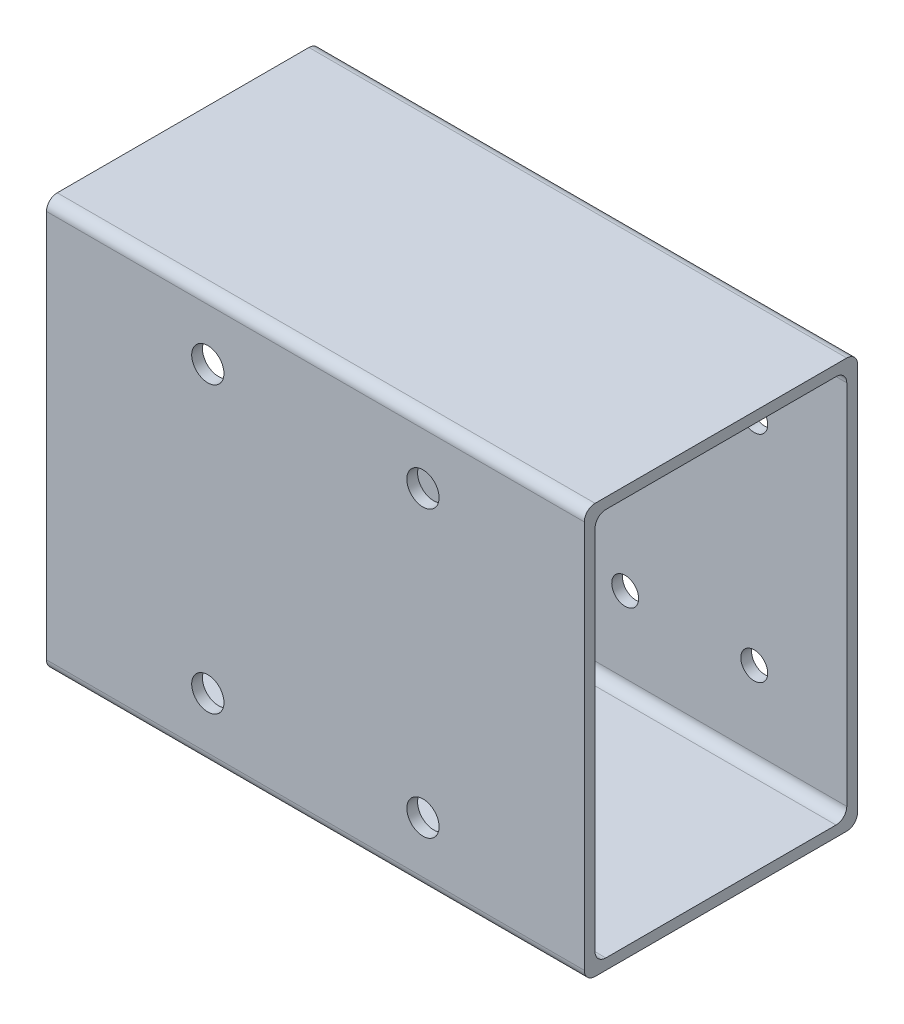
SolidWorks part; units mm, degrees
material "A500"
ref_plane "Alzado" through (0, 0, 0) normal (0, 0, 1) x (1, 0, 0)
ref_plane "Planta" through (0, 0, 0) normal (0, 1, 0) x (1, 0, 0)
ref_plane "Vista lateral" through (0, 0, 0) normal (1, 0, 0) x (0, 0, -1)
sketch "Sketch1" plane through (0, 0, 0) normal (1, 0, 0) x (0, 0, -1)
  line L1 (25.4, 38.1) -> (-25.4, 38.1)
  line L2 (25.4, 38.1) -> (25.4, -38.1)
  line L3 (25.4, -38.1) -> (-25.4, -38.1)
  line L4 (-25.4, 38.1) -> (-25.4, -38.1)
  line L5 (25.4, 38.1) -> (-25.4, -38.1) construction
  line L6 (25.4, -38.1) -> (-25.4, 38.1) construction
  point P0 (0, 0)
  dimension "D1" = 76.2
  dimension "D2" = 50.8
extrude "Boss-Extrude1" add sketch "Sketch1" against normal blind 100
sketch "Sketch2" plane through (0, 0, 0) normal (1, 0, 0) x (0, 0, -1)
  line L0 (25.4, 38.1) -> (-25.4, 38.1) construction
  line L1 (23.4, 36.1) -> (-23.4, 36.1)
  line L2 (23.4, 36.1) -> (23.4, -36.1)
  line L3 (23.4, -36.1) -> (-23.4, -36.1)
  line L4 (-23.4, 36.1) -> (-23.4, -36.1)
  line L5 (23.4, 36.1) -> (-23.4, -36.1) construction
  line L6 (23.4, -36.1) -> (-23.4, 36.1) construction
  line L7 (25.4, -38.1) -> (25.4, 38.1) construction
  point P0 (0, 0)
  dimension "D1" = 2
  dimension "D2" = 2
extrude "Cut-Extrude1" cut sketch "Sketch2" against normal through all
fillet "Fillet2" radius 2 8 edges at (-50, -38.1, -25.4) (-50, -38.1, 25.4) (-50, 38.1, 25.4) (-50, 38.1, -25.4) (-50, -36.1, -23.4) (-50, 36.1, -23.4) (-50, -36.1, 23.4) (-50, 36.1, 23.4)
sketch "Croquis2" plane through (0, 0, 25.4) normal (0, 0, 1) x (1, 0, 0)
  line L0 (-50, 36.1) -> (-50, -36.1) construction
  line L1 (0, 36.1) -> (-100, 36.1) construction
  line L2 (-100, -36.1) -> (0, -36.1) construction
  line L4 (-30, 26.5) -> (-70, 26.5)
  line L5 (-30, 26.5) -> (-30, -26.5)
  line L6 (-30, -26.5) -> (-70, -26.5)
  line L7 (-70, 26.5) -> (-70, -26.5)
  line L8 (-30, 26.5) -> (-70, -26.5) construction
  line L9 (-30, -26.5) -> (-70, 26.5) construction
  circle A0 centre (-70, 26.5) radius 3
  circle A1 centre (-30, 26.5) radius 3
  circle A2 centre (-30, -26.5) radius 3
  circle A3 centre (-70, -26.5) radius 3
  point P6 (-50, 0)
  dimension "D3" = 6
  dimension "D4" = 6
  dimension "D5" = 6
  dimension "D6" = 6
  dimension "D1" = 53
  dimension "D2" = 40
extrude "Cortar-Extruir2" cut sketch "Croquis2" against normal blind 10 contours L5 A1 L4 | L4 A1 L5 | L4 A0 L7 | L7 A0 L4 | L6 A3 L7 | L7 A3 L6 | L6 A2 L5 | L5 A2 L6
sketch "Croquis4" plane through (0, 0, -25.4) normal (0, 0, -1) x (-1, 0, 0)
  line L0 (49.2, 38.1) -> (49.2, -38.1) construction
  line L2 (0, 38.1) -> (100, 38.1) construction
  line L3 (100, -38.1) -> (0, -38.1) construction
  line L6 (100, -36.1) -> (100, 36.1) construction
  line L7 (100, 20) -> (49.2, 20) construction
  line L8 (100, -20) -> (49.2, -20) construction
  line L9 (49.2, 0) -> (100, 0) construction
  circle A1 centre (90, 20) radius 2.5
  circle A2 centre (59.2, 20) radius 2.5
  circle A3 centre (59.2, -20) radius 2.5
  circle A4 centre (90, -20) radius 2.5
  circle A5 centre (74.6, 0) radius 2.5
  dimension "D3" = 20
  dimension "D4" = 5
  dimension "D5" = 5
  dimension "D6" = 5
  dimension "D7" = 5
  dimension "D8" = 5
  dimension "D1" = 50.8
  dimension "D2" = 20
  dimension "D9" = 10
  dimension "D10" = 10
  dimension "D11" = 10
  dimension "D12" = 10
extrude "Cortar-Extruir5" cut sketch "Croquis4" against normal blind 10
sketch "Croquis6" plane through (0, 0, -25.4) normal (0, 0, -1) x (-1, 0, 0)
  line L0 (49.2, 38.1) -> (49.2, -38.1) construction
  line L8 (0, 0) -> (41.2, 0) construction
  line L9 (41.2, 20) -> (17.2, 20)
  line L10 (41.2, 20) -> (41.2, -20)
  line L11 (41.2, -20) -> (17.2, -20)
  line L12 (17.2, 20) -> (17.2, -20)
  line L13 (0, -36.1) -> (0, 36.1) construction
  line L14 (0, 38.1) -> (100, 38.1) construction
  line L15 (100, -38.1) -> (0, -38.1) construction
  line L16 (100, -36.1) -> (100, 36.1) construction
  circle A0 centre (17.2, 20) radius 2.5
  circle A1 centre (17.2, -20) radius 2.5
  circle A2 centre (41.2, -20) radius 2.5
  circle A3 centre (41.2, 20) radius 2.5
  dimension "D5" = 5
  dimension "D6" = 5
  dimension "D7" = 5
  dimension "D8" = 5
  dimension "D1" = 8
  dimension "D2" = 24
  dimension "D3" = 40
  dimension "D4" = 20
  dimension "D9" = 50.8
extrude "Cortar-Extruir6" cut sketch "Croquis6" against normal blind 10 contours A0 | A3 | A2 | A1
sketch "Croquis7" plane through (0, -38.1, 0) normal (0, -1, 0) x (1, 0, 0)
  line L0 (0, 0.4) -> (-100, 0.4) construction
  line L1 (0, 23.4) -> (0, -23.4) construction
  line L2 (-100, 23.4) -> (-100, -23.4) construction
  line L3 (-100, 25.4) -> (0, 25.4) construction
  circle A0 centre (-15, 0.4) radius 2.5
  circle A1 centre (-85, 0.4) radius 2.5
  dimension "D2" = 5
  dimension "D5" = 5
  dimension "D1" = 25
  dimension "D3" = 15
  dimension "D4" = 15
extrude "Cortar-Extruir7" [suppressed] cut sketch "Croquis7" against normal blind 10
